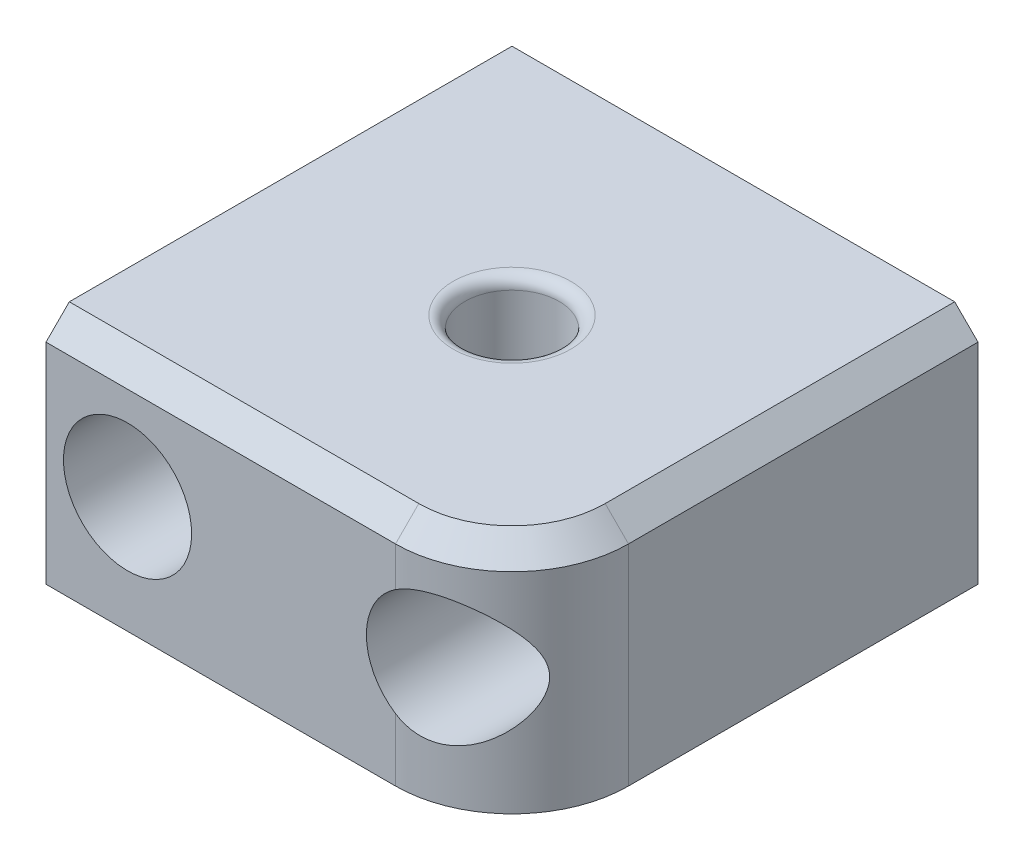
SolidWorks part; units mm, degrees
ref_plane "Front Plane" through (0, 0, 0) normal (0, 0, 1) x (1, 0, 0)
ref_plane "Top Plane" through (0, 0, 0) normal (0, 1, 0) x (1, 0, 0)
ref_plane "Right Plane" through (0, 0, 0) normal (1, 0, 0) x (0, 0, -1)
sketch "Sketch1" plane through (0, 0, 0) normal (0, 1, 0) x (1, 0, 0)
  line L1 (10, -20) -> (-20, -20)
  line L2 (20, -10) -> (20, 20)
  line L3 (20, 20) -> (-20, 20)
  line L4 (-20, -20) -> (-20, 20)
  line L5 (20, -20) -> (-20, 20) construction
  line L6 (20, 20) -> (-20, -20) construction
  arc A0 (10, -20) -> (20, -10) centre (10, -10) ccw
  circle A1 centre (0, 0) radius 4.05
  point P0 (0, 0)
  dimension "D3" = 10
  dimension "D4" = 8.1
  dimension "D1" = 40
  dimension "D2" = 40
extrude "Boss-Extrude1" add sketch "Sketch1" along normal blind 20
sketch "Sketch2" plane through (20, 0, 0) normal (1, 0, 0) x (0, 0, -1)
  line L0 (20, 20) -> (20, 0) construction
  circle A0 centre (13, 10) radius 2.65
  dimension "D1" = 5.3
  dimension "D2" = 7
sketch "Sketch3" plane through (0, 0, 20) normal (0, 0, 1) x (1, 0, 0)
  line L0 (-20, 10) -> (-6, 10) construction
  line L1 (-20, 20) -> (-20, 0) construction
  line L2 (0, 0) -> (0, 20) construction
  line L3 (-20, 20) -> (10, 20) construction
  circle A0 centre (-13, 10) radius 2.65
  circle A1 centre (13, 10) radius 2.65
  dimension "D1" = 5.3
  dimension "D2" = 7
extrude "Cut-Extrude5" cut sketch "Sketch3" against normal blind 40 contours A0 | A1
sketch "Sketch6" plane through (0, 0, 20) normal (0, 0, 1) x (1, 0, 0)
  circle A0 centre (-13, 10) radius 5.5
  circle A1 centre (13, 10) radius 5.5
  dimension "D1" = 11
  dimension "D2" = 11
extrude "Cut-Extrude7" cut sketch "Sketch6" against normal blind 29
chamfer "Chamfer1" distance 2 angle 45 3 edges at (20, 20, -5) (17.0711, 20, 17.0711) (-5, 20, 20)
fillet "Fillet1" radius 1 1 edges at (0, 20, 4.05)
